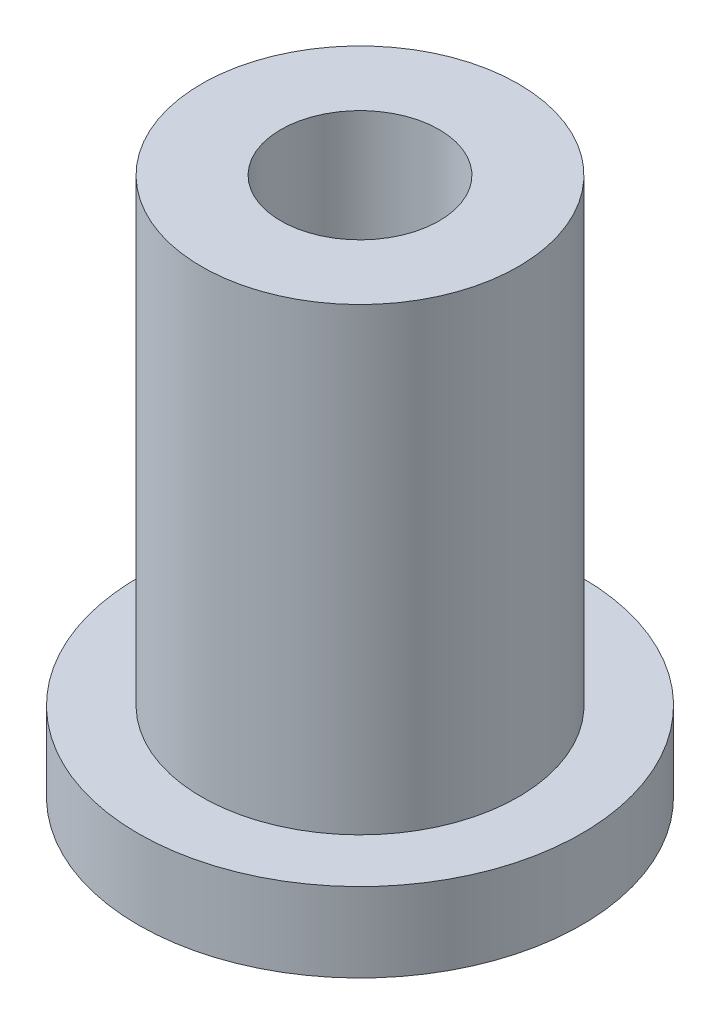
SolidWorks part; units mm, degrees
ref_plane "Plan de face" through (0, 0, 0) normal (0, 0, 1) x (1, 0, 0)
ref_plane "Plan de dessus" through (0, 0, 0) normal (0, 1, 0) x (1, 0, 0)
ref_plane "Plan de droite" through (0, 0, 0) normal (1, 0, 0) x (0, 0, -1)
sketch "Esquisse1" plane through (0, 0, 0) normal (0, 0, 1) x (1, 0, 0)
  line L0 (-5, 0) -> (-5, 34)
  line L1 (-5, 34) -> (-10, 34)
  line L2 (-10, 34) -> (-10, 5)
  line L3 (-10, 5) -> (-14, 5)
  line L4 (-14, 5) -> (-14, 0)
  line L5 (-14, 0) -> (-5, 0)
  line L6 (0, 0) -> (0, 54.7658) construction
  dimension "D1" = 5
  dimension "D2" = 10
  dimension "D3" = 34
  dimension "D4" = 5
  dimension "D5" = 14
revolve "Révolution1" add sketch "Esquisse1" angle 360 about L6
